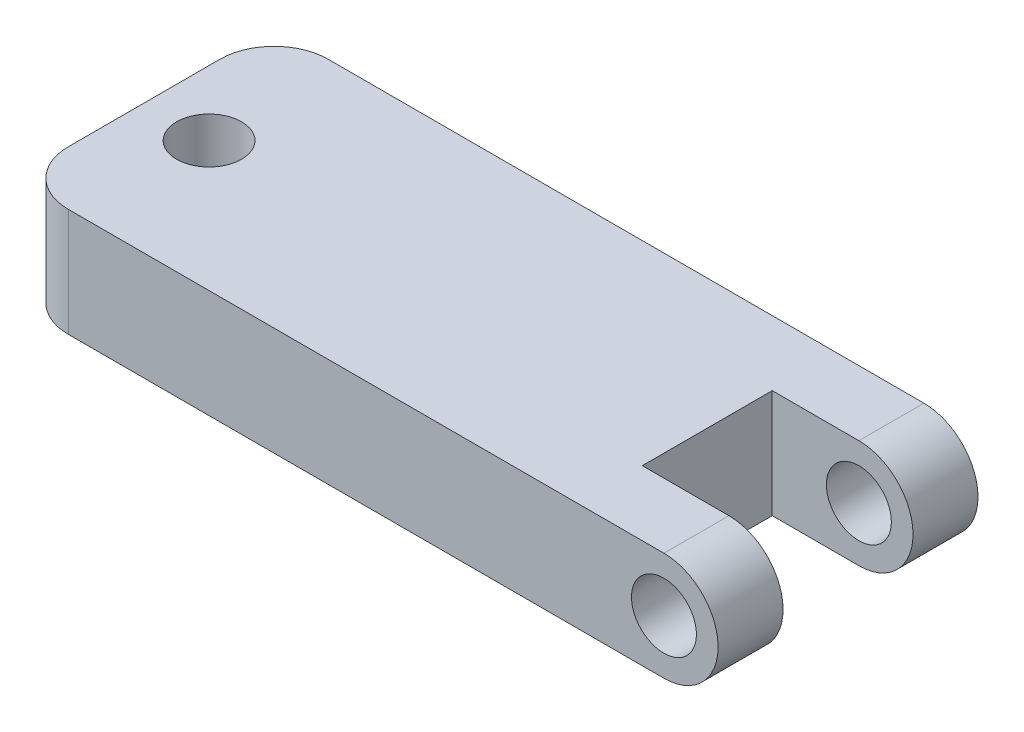
SolidWorks part; units mm, degrees
ref_plane "Front Plane" through (0, 0, 0) normal (0, 0, 1) x (1, 0, 0)
ref_plane "Top Plane" through (0, 0, 0) normal (0, 1, 0) x (1, 0, 0)
ref_plane "Right Plane" through (0, 0, 0) normal (1, 0, 0) x (0, 0, -1)
sketch "Sketch1" plane through (0, 0, 0) normal (0, 0, 1) x (1, 0, 0)
  line L0 (0, 0) -> (30, 0)
  line L1 (30, 5) -> (0, 5)
  line L2 (0, 5) -> (0, 0)
  arc A0 (30, 0) -> (30, 5) centre (30, 2.5) ccw
  dimension "D2" = 2.5
  dimension "D1" = 30
extrude "Boss-Extrude1" add sketch "Sketch1" against normal blind 12
sketch "Sketch2" plane through (0, 5, 0) normal (0, 1, 0) x (1, 0, 0)
  line L0 (32.5, 0) -> (32.5, 12) construction
  line L1 (26, 9) -> (32.5, 9)
  line L2 (26, 9) -> (26, 3)
  line L3 (26, 3) -> (32.5, 3)
  line L4 (32.5, 9) -> (32.5, 3)
  line L5 (30, 12) -> (0, 12) construction
  line L7 (30, 12) -> (30, 0) construction
  dimension "D1" = 6
  dimension "D2" = 3
  dimension "D3" = 4
extrude "Cut-Extrude1" cut sketch "Sketch2" against normal through all
sketch "Sketch3" plane through (0, 0, 0) normal (0, 0, 1) x (1, 0, 0)
  circle A0 centre (30, 2.5) radius 1.5
  dimension "D1" = 3
extrude "Cut-Extrude2" cut sketch "Sketch3" against normal blind 12
sketch "Sketch6" plane through (0, 5, 0) normal (0, 1, 0) x (1, 0, 0)
  line L0 (0, 12) -> (0, 0) construction
  line L3 (30, 0) -> (0, 0) construction
  circle A0 centre (3, 6) radius 1.5
  point P4 (4.4292, 7.2708)
  dimension "D1" = 3
  dimension "D2" = 3
  dimension "D3" = 6
extrude "Cut-Extrude3" cut sketch "Sketch6" against normal through all
fillet "Fillet1" radius 2.5 2 edges at (0, 2.5, -12) (0, 2.5, 0)
